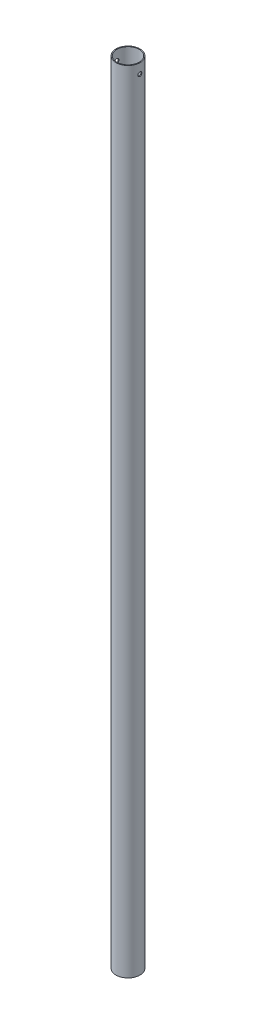
SolidWorks part; units mm, degrees
ref_plane "Front Plane" through (0, 0, 0) normal (0, 0, 1) x (1, 0, 0)
ref_plane "Top Plane" through (0, 0, 0) normal (0, 1, 0) x (1, 0, 0)
ref_plane "Right Plane" through (0, 0, 0) normal (1, 0, 0) x (0, 0, -1)
sketch "Sketch1" plane through (0, 0, 0) normal (0, 1, 0) x (1, 0, 0)
  circle A0 centre (0, 0) radius 30
  dimension "D1" = 60
extrude "Extrude-Thin1" add sketch "Sketch1" along normal mid plane 1981 thin thin type one direction reverse wall 2
sketch "Sketch2" plane through (0, 0, 0) normal (1, 0, 0) x (0, 0, -1)
  line L0 (28, 990.5) -> (-28, 990.5) construction
  circle A0 centre (0, 965.5) radius 5
  dimension "D1" = 10
  dimension "D2" = 25
extrude "Cut-Extrude1" cut sketch "Sketch2" against normal through all both and the other way through all
